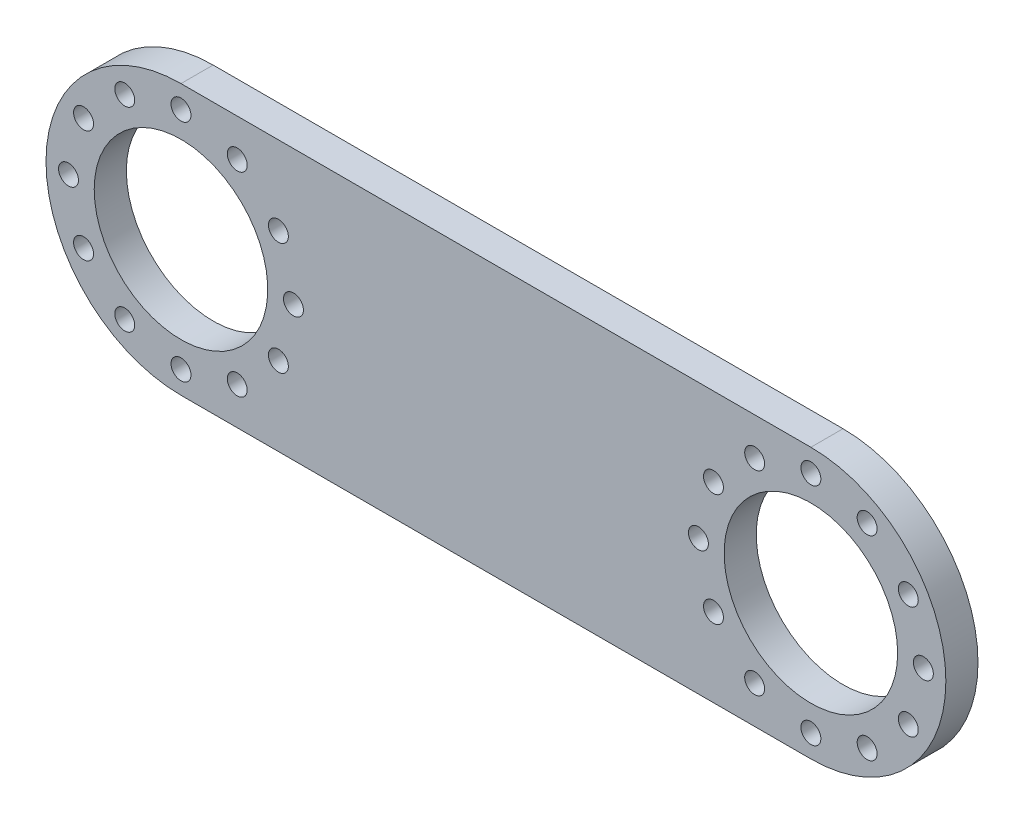
SolidWorks part; units mm, degrees
material "Thornel Mat VMA"
ref_plane "前视基准面" through (0, 0, 0) normal (0, 0, 1) x (1, 0, 0)
ref_plane "上视基准面" through (0, 0, 0) normal (0, 1, 0) x (1, 0, 0)
ref_plane "右视基准面" through (0, 0, 0) normal (1, 0, 0) x (0, 0, -1)
sketch "草图1" plane through (0, 0, 0) normal (0, 0, 1) x (1, 0, 0)
  line L0 (-49, 0) -> (49, 0) construction
  line L1 (-49, -21) -> (49, -21)
  line L2 (-49, 21) -> (49, 21)
  arc A0 (49, -21) -> (49, 21) centre (49, 0) ccw
  arc A1 (-49, 21) -> (-49, -21) centre (-49, 0) ccw
  point P4 (0, 0)
  dimension "D2" = 42
  dimension "D1" = 98
extrude "凸台-拉伸1" add sketch "草图1" along normal blind 5
sketch "草图2" plane through (0, 0, 5) normal (0, 0, 1) x (1, 0, 0)
  line L0 (0, 0) -> (0, 21) construction
  line L1 (49, 21) -> (-49, 21) construction
  circle A0 centre (49, 0) radius 13.5
  circle A1 centre (49, 0) radius 17.5 construction
  circle A2 centre (49, 17.5) radius 1.55
  circle A3 centre (57.75, 15.1554) radius 1.55
  circle A4 centre (64.1554, 8.75) radius 1.55
  circle A5 centre (66.5, 0) radius 1.55
  circle A6 centre (64.1554, -8.75) radius 1.55
  circle A7 centre (57.75, -15.1554) radius 1.55
  circle A8 centre (49, -17.5) radius 1.55
  circle A9 centre (40.25, -15.1554) radius 1.55
  circle A10 centre (33.8446, -8.75) radius 1.55
  circle A11 centre (31.5, 0) radius 1.55
  circle A12 centre (33.8446, 8.75) radius 1.55
  circle A13 centre (40.25, 15.1554) radius 1.55
  point P31 (49, 0)
  dimension "D1" = 27
  dimension "D2" = 35
  dimension "D3" = 3.1
  dimension "D4" = 12
extrude "切除-拉伸1" cut sketch "草图2" against normal blind 5
mirror "镜向1" about plane through (0, 0, 0) normal (1, 0, 0) of "切除-拉伸1"
sketch "草图5" [suppressed] plane through (0, 0, 5) normal (0, 0, 1) x (1, 0, 0)
  line L5 (49, 21) -> (-49, 21) construction
  line L6 (-37, 71) -> (37, 71) construction
  line L7 (-37, 71) -> (-37, 21) construction
  line L8 (-37, 21) -> (37, 21) construction
  line L9 (37, 71) -> (37, 21) construction
  line L10 (0, 21) -> (0, 71) construction
  line L11 (-37, 46) -> (37, 46) construction
  line L12 (0, 21) -> (0, 0) construction
  line L13 (53.1303, 36.4503) -> (87.9235, 11.4167)
  line L14 (87.9235, 11.4167) -> (66.9897, -41.5341)
  circle A0 centre (49, 0) radius 30 construction
  circle A1 centre (49, 0) radius 32 construction
  point P3 (0, 46)
  dimension "D1" = 60
  dimension "D4" = 2
  dimension "D2" = 74
  dimension "D3" = 50
sketch "草图6" [suppressed] plane through (0, 0, 5) normal (0, 0, 1) x (1, 0, 0)
  line L1 (-14, 13) -> (14, 13) construction
  line L2 (-14, 13) -> (-14, -13) construction
  line L3 (-14, -13) -> (14, -13) construction
  line L4 (14, 13) -> (14, -13) construction
  line L5 (-14, 13) -> (14, -13) construction
  line L6 (-14, -13) -> (14, 13) construction
  circle A0 centre (14, -13) radius 1.6
  circle A1 centre (-14, -13) radius 1.6
  circle A2 centre (-14, 13) radius 1.6
  circle A3 centre (14, 13) radius 1.6
  point P0 (0, 0)
  dimension "D3" = 3.2
  dimension "D1" = 28
  dimension "D2" = 26
extrude "切除-拉伸2" [suppressed] cut sketch "草图6" against normal blind 10
